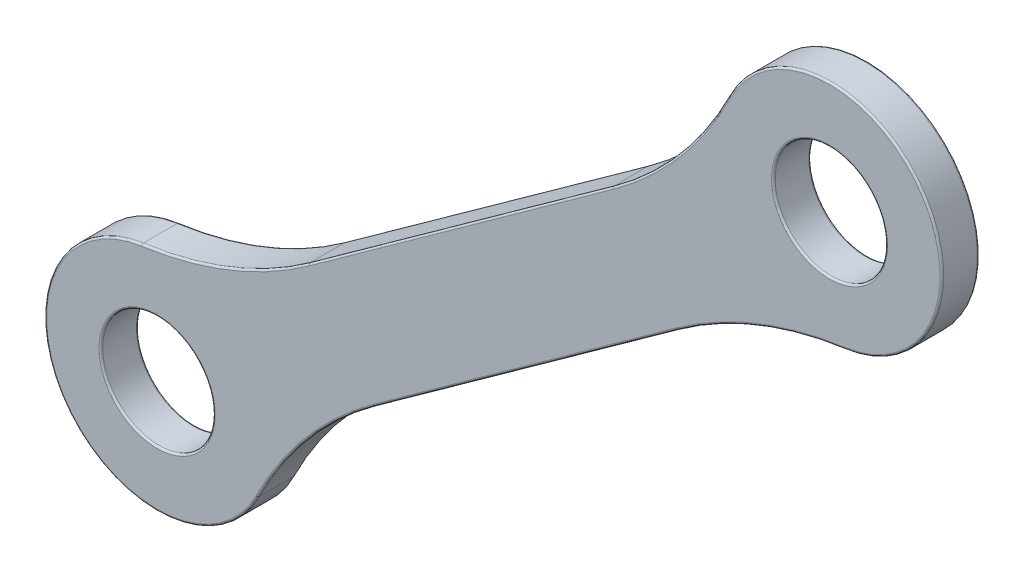
SolidWorks part; units mm, degrees
material "Plain Carbon Steel"
ref_plane "Front Plane" through (0, 0, 0) normal (0, 0, 1) x (1, 0, 0)
ref_plane "Top Plane" through (0, 0, 0) normal (0, 1, 0) x (1, 0, 0)
ref_plane "Right Plane" through (0, 0, 0) normal (1, 0, 0) x (0, 0, -1)
sketch "Sketch1" plane through (0, 0, 0) normal (0, 0, 1) x (1, 0, 0)
  line L0 (16.9307, 91.8876) -> (70.775, 130.5624) construction
  line L1 (16.9307, 91.8876) -> (70.775, 130.5624) construction
  line L2 (16.9307, 91.8876) -> (70.775, 130.5624) construction
  line L3 (14.3055, 95.5425) -> (68.1498, 134.2173)
  line L4 (19.5559, 88.2327) -> (73.4002, 126.9075)
  circle A0 centre (16.9307, 91.8876) radius 9
  circle A1 centre (70.775, 130.5624) radius 9
  arc A2 (14.3055, 95.5425) -> (19.5559, 88.2327) centre (16.9307, 91.8876) ccw
  arc A3 (73.4002, 126.9075) -> (68.1498, 134.2173) centre (70.775, 130.5624) ccw
  arc A4 (68.1498, 134.2173) -> (73.4002, 126.9075) centre (70.775, 130.5624) ccw
  arc A5 (14.3055, 95.5425) -> (19.5559, 88.2327) centre (16.9307, 91.8876) cw
  point P5 (43.8529, 111.225)
  dimension "D1" = 18
  dimension "D2" = 9
extrude "Boss-Extrude1" add sketch "Sketch1" along normal blind 3 contours A3 L4 A1 L3 | A1 L3 A0 L4 | A2 L3 A0 L4 | L3 A5 L4 A0 | A4 L3 A1 L4
fillet "Fillet1" radius 30 4 edges at (20.636, 100.0894, 1.5) (25.8864, 92.7797, 1.5) (67.0698, 122.3605, 1.5) (61.8194, 129.6703, 1.5)
fillet "Fillet2" radius 0.15 20 edges at (21.4307, 91.8876, 3) (21.4307, 91.8876, 0) (75.275, 130.5624, 3) (75.275, 130.5624, 0) (28.9868, 93.9253, 3) (28.9868, 93.9253, 0) (46.4781, 107.5701, 3) (46.4781, 107.5701, 0) (64.994, 119.7882, 3) (64.994, 119.7882, 0) (78.0848, 135.8128, 3) (78.0848, 135.8128, 0) (58.7189, 128.5246, 3) (58.7189, 128.5246, 0) (41.2277, 114.8799, 0) (41.2277, 114.8799, 3) (22.7117, 102.6617, 3) (22.7117, 102.6617, 0) (9.6209, 86.6371, 3) (9.6209, 86.6371, 0)
